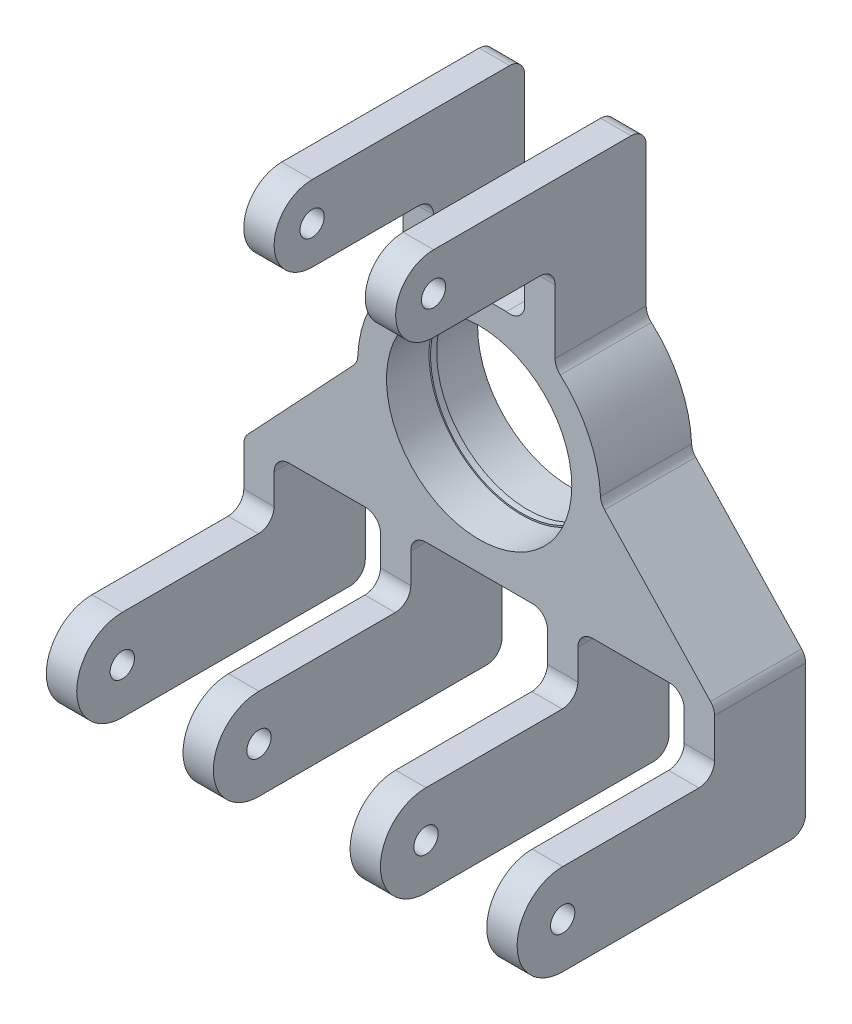
SolidWorks part; units mm, degrees
ref_plane "Front Plane" through (0, 0, 0) normal (0, 0, 1) x (1, 0, 0)
ref_plane "Top Plane" through (0, 0, 0) normal (0, 1, 0) x (1, 0, 0)
ref_plane "Right Plane" through (0, 0, 0) normal (1, 0, 0) x (0, 0, -1)
sketch "Sketch1" plane through (0, 0, 0) normal (0, 0, 1) x (1, 0, 0)
  line L0 (-15, 84.641) -> (-15, 43.7894)
  line L1 (0, -40) -> (0, -90) construction
  line L2 (15, 84.641) -> (25, 84.641)
  line L3 (76.1661, -38.5772) -> (41.2895, -1.3754)
  line L4 (67.5, -90) -> (77.5, -90)
  line L5 (25, 84.641) -> (25, 33.6115)
  line L6 (-25, 84.641) -> (-25, 33.6115)
  line L7 (-37.432, -40) -> (-62.568, -40)
  line L8 (15, 84.641) -> (15, 43.7894)
  line L9 (-25, 84.641) -> (-15, 84.641)
  line L10 (22.5, -90) -> (32.5, -90)
  line L11 (77.5, -90) -> (77.5, -41.9503)
  line L12 (67.5, -90) -> (67.5, -44.932)
  line L14 (32.5, -90) -> (32.5, -44.932)
  line L15 (37.432, -40) -> (62.568, -40)
  line L16 (22.5, -90) -> (22.5, -44.932)
  line L17 (-32.5, -90) -> (-22.5, -90)
  line L18 (17.568, -40) -> (-17.568, -40)
  line L19 (-22.5, -44.932) -> (-22.5, -90)
  line L20 (-77.5, -90) -> (-67.5, -90)
  line L21 (-32.5, -90) -> (-32.5, -44.932)
  line L22 (-67.5, -44.932) -> (-67.5, -90)
  line L23 (-8.9629, 38.9829) -> (8.9629, 38.9829)
  line L24 (-77.5, -90) -> (-77.5, -41.9503)
  line L25 (-76.1661, -38.5772) -> (-41.2895, -1.3754)
  line L26 (70.6196, -14.9692) -> (62.568, -24.0726)
  line L29 (31.5757, 50.4604) -> (25, 33.6115)
  circle A0 centre (0, 0) radius 31
  arc A1 (39.9604, 1.7784) -> (26.7132, 29.7725) centre (0, 0) ccw
  arc A2 (-77.5, -41.9503) -> (-76.1661, -38.5772) centre (-72.568, -41.9503) cw
  arc A3 (77.5, -41.9503) -> (76.1661, -38.5772) centre (72.568, -41.9503) ccw
  arc A4 (67.5, -44.932) -> (62.568, -40) centre (62.568, -44.932) ccw
  arc A5 (37.432, -40) -> (32.5, -44.932) centre (37.432, -44.932) ccw
  arc A6 (22.5, -44.932) -> (17.568, -40) centre (17.568, -44.932) ccw
  arc A7 (-17.568, -40) -> (-22.5, -44.932) centre (-17.568, -44.932) ccw
  arc A8 (-32.5, -44.932) -> (-37.432, -40) centre (-37.432, -44.932) ccw
  arc A9 (-62.568, -40) -> (-67.5, -44.932) centre (-62.568, -44.932) ccw
  arc A11 (-26.7132, 29.7725) -> (-39.9604, 1.7784) centre (0, 0) ccw
  arc A12 (-39.9604, 1.7784) -> (-41.2895, -1.3754) centre (-44.8875, 1.9977) cw
  arc A13 (41.2895, -1.3754) -> (39.9604, 1.7784) centre (44.8875, 1.9977) cw
  arc A14 (15, 43.7894) -> (8.9629, 38.9829) centre (10.068, 43.7894) cw
  arc A15 (-15, 43.7894) -> (-8.9629, 38.9829) centre (-10.068, 43.7894) ccw
  arc A16 (26.7132, 29.7725) -> (25, 33.6115) centre (30.1577, 33.6115) cw
  arc A17 (-26.7132, 29.7725) -> (-25, 33.6115) centre (-30.1577, 33.6115) ccw
  circle A21 centre (65.0017, -10.0004) radius 7.5
  circle A22 centre (65.0017, -10.0004) radius 5
  circle A24 centre (38.5625, 47.7336) radius 7.5
  circle A25 centre (38.5625, 47.7336) radius 5
  arc A26 (44.835, 43.6219) -> (65.9863, -2.5653) centre (69.9248, 27.175) ccw
  point P7 (0, 40)
  point P12 (-20, 84.641)
  point P15 (-20, 84.641)
  point P17 (-77.5, -40)
  point P18 (20, 84.641)
  point P22 (77.5, -40)
  point P27 (20, 84.641)
  point P32 (0, -90)
  point P33 (27.5, -90)
  point P35 (-27.5, -90)
  point P38 (72.5, -90)
  point P41 (27.5, -90)
  point P48 (-27.5, -90)
  point P52 (-72.5, -90)
  point P63 (-40, 0)
  point P66 (40, 0)
  point P69 (15, 37.081)
  point P72 (-15, 37.081)
  point P77 (-25, 31.225)
  point P78 (56.685, -17.7973)
  dimension "D1" = 80
  dimension "D2" = 62
  dimension "D3" = 4.932
  dimension "D4" = 10
  dimension "D8" = 4.932
  dimension "D6" = 4.932
  dimension "D7" = 4.932
  dimension "D10" = 5.1577
  dimension "D11" = 22.51
  dimension "D18" = 15
  dimension "D19" = 10
  dimension "D22" = 15
  dimension "D23" = 10
  dimension "D16" = 30
  dimension "D5" = 50
  dimension "D9" = 10
  dimension "D12" = 10
  dimension "D13" = 10
  dimension "D14" = 50
  dimension "D15" = 10
  dimension "D20" = 63.5
  dimension "D21" = 19.58
extrude "Boss-Extrude2" add sketch "Sketch1" along normal blind 30 contours L23 A14 L8 L2 L5 A16 A1 A13 L3 A3 L11 L4 L12 A4 L15 A5 L14 L10 L16 A6 L18 A7 L19 L17 L21 A8 L7 A9 L22 L20 L24 A2 L25 A12 A11 A17 L6 L9 L0 A15
sketch3d "3DSketch1"
  line L0 (25, 33.6115, 0) -> (55.1201, 33.6115, 0)
  line L1 (37.5535, 42.2929, 0) -> (47.5535, 42.2929, 0) construction
  line L2 (42.5535, 47.2929, 0) -> (42.5535, 37.2929, 0) construction
  line L3 (58.9178, -17.2632, 0) -> (70.2491, -17.2632, 0) construction
  line L4 (74.516, -36.8171, 0) -> (41.2895, -1.3754, 0)
  line L5 (64.5834, -11.5976, 0) -> (64.5834, -22.9289, 0) construction
  line L6 (78.9863, -32.6262, 0) -> (74.516, -36.8171, 0)
  line L7 (36.9074, 47.2297, 0) -> (25, 33.6115, 0)
  line L8 (25, 33.6115, 0) -> (42.5535, 42.2929, 0)
  circle A1 centre (42.5535, 42.2929, 0) radius 5
  circle A4 centre (64.5834, -17.2632, 0) radius 5.6657
  circle A5 centre (42.5535, 42.2929, 0) radius 7.5
  arc A6 (48.0997, 37.2442, 0) -> (57.9491, 2.723, 0) centre (61.5074, 22.4039, 0) cw
  arc A8 (25, 33.6115, 0) -> (26.7132, 29.7725, 0) centre (30.1577, 33.6115, 0) cw
  circle A9 centre (64.5834, -17.2632, 0) radius 21.0586
  arc A10 (26.7132, 29.7725, 0) -> (39.9604, 1.7784, 0) centre (0, 0, 0) ccw
  arc A11 (41.2895, -1.3754, 0) -> (39.9604, 1.7784, 0) centre (44.8875, 1.9977, 0) ccw
  point P7 (42.5535, 42.2929, 0)
  point P8 (42.5535, 42.2929, 0)
  point P11 (42.5535, 42.2929, 5)
  point P17 (64.5834, -17.2632, 5.6657)
  point P20 (42.5535, 42.2929, 0)
  point P24 (64.5834, -17.2632, 0)
  point P27 (64.5834, -17.2632, 0)
  point P29 (64.5834, -17.2632, 21.0586)
  point P31 (42.5535, 42.2929, 7.5)
  point P39 (61.5074, 22.4039, 20)
  point P45 (30.1577, 33.6115, 5.1577)
  point P49 (0, 0, -40)
  point P53 (44.8875, 1.9977, -4.932)
  dimension "D2" = 63.5
  dimension "D1" = 26.316
sketch "Sketch2" plane through (-77.5, 0, 0) normal (-1, 0, 0) x (0, 0, 1)
  line L0 (30, -90) -> (80, -90)
  line L1 (30, -90) -> (4.932, -90)
  line L2 (80, -60) -> (35.1577, -60)
  line L3 (30, -41.9503) -> (30, -90) construction
  line L4 (0, -85.068) -> (0, -41.9503)
  line L5 (30, -54.8423) -> (30, -41.9503)
  arc A0 (80, -90) -> (80, -60) centre (80, -75) ccw
  circle A1 centre (80, -75) radius 4
  arc A2 (4.932, -90) -> (0, -85.068) centre (4.932, -85.068) cw
  arc A3 (35.1577, -60) -> (30, -54.8423) centre (35.1577, -54.8423) cw
  point P16 (0, -90)
  point P21 (30, -60)
  line M6 (30, -90) -> (30, -41.9503)
  dimension "D3" = 8
  dimension "D4" = 4.932
  dimension "D5" = 5.1577
  dimension "D1" = 50
  dimension "D2" = 30
extrude "Boss-Extrude3" add sketch "Sketch2" against normal blind 10 contours L0 A0 L2 A1 M6
sketch "Sketch3" plane through (-77.5, 0, 0) normal (-1, 0, 0) x (0, 0, 1)
  line L0 (0, -85) -> (0, -66.5929)
  line L1 (0, -41.9503) -> (0, -90) construction
  line L2 (5, -90) -> (19.0875, -90)
  line L3 (80, -90) -> (0, -90) construction
  line L4 (0, -85) -> (0, -90)
  line L5 (0, -90) -> (5, -90)
  arc A0 (5, -90) -> (0, -85) centre (5, -85) cw
  point P10 (0, -90)
  line M4 (0, -41.9503) -> (0, -90)
  line M5 (0, -90) -> (80, -90)
  dimension "D1" = 5
extrude "Cut-Extrude3" cut sketch "Sketch3" against normal blind 162 contours A0 M5 M4
sketch "Sketch4" plane through (-32.5, 0, 0) normal (-1, 0, 0) x (0, 0, 1)
  line L0 (30, -90) -> (80, -90)
  line L1 (80, -60) -> (35.1577, -60)
  arc A0 (80, -90) -> (80, -60) centre (80, -75) ccw
  circle A1 centre (80, -75) radius 4
  arc A2 (35.1577, -60) -> (30, -54.8423) centre (35.1577, -54.8423) cw
  line M7 (30, -90) -> (30, -44.932)
  dimension "D1" = 30
  dimension "D2" = 8
extrude "Boss-Extrude4" add sketch "Sketch4" against normal blind 10 contours L1 A2 L0 A0 A1 M7
sketch "Sketch5" plane through (22.5, 0, 0) normal (-1, 0, 0) x (0, 0, 1)
  line L0 (30, -90) -> (80, -90)
  line L1 (80, -60) -> (35.1577, -60)
  arc A0 (80, -90) -> (80, -60) centre (80, -75) ccw
  circle A1 centre (80, -75) radius 4
  arc A2 (35.1577, -60) -> (30, -54.8423) centre (35.1577, -54.8423) cw
  line M4 (30, -90) -> (30, -44.932)
  dimension "D1" = 8
extrude "Boss-Extrude5" add sketch "Sketch5" against normal blind 10 contours L1 A2 L0 A0 A1 M4
sketch "Sketch6" plane through (67.5, 0, 0) normal (-1, 0, 0) x (0, 0, 1)
  line L0 (30, -90) -> (80, -90)
  line L1 (80, -60) -> (35.1577, -60)
  arc A0 (80, -90) -> (80, -60) centre (80, -75) ccw
  circle A1 centre (80, -75) radius 4
  arc A2 (35.1577, -60) -> (30, -54.8423) centre (35.1577, -54.8423) cw
  line M4 (30, -90) -> (30, -44.932)
  dimension "D1" = 8
extrude "Boss-Extrude6" add sketch "Sketch6" against normal blind 10 contours L1 A2 L0 A0 A1 M4
sketch "Sketch7" plane through (-25, 0, 0) normal (-1, 0, 0) x (0, 0, 1)
  line L0 (30, 84.641) -> (70, 84.641)
  line L1 (30, 54.641) -> (30, 49.8065)
  line L2 (70, 59.641) -> (35, 59.641)
  line L3 (30, 84.641) -> (30, 33.6115) construction
  line L4 (30, 84.641) -> (30, 33.6115) construction
  arc A0 (70, 59.641) -> (70, 84.641) centre (70, 72.141) ccw
  circle A1 centre (70, 72.141) radius 4
  arc A2 (30, 54.641) -> (35, 59.641) centre (35, 54.641) cw
  point P14 (30, 59.641)
  line M5 (30, 33.6115) -> (30, 84.641)
  dimension "D3" = 8
  dimension "D4" = 5
  dimension "D1" = 40
  dimension "D2" = 25
extrude "Boss-Extrude7" add sketch "Sketch7" against normal blind 10 contours L2 A0 L0 A1 M5
sketch "Sketch9" plane through (-25, 0, 0) normal (-1, 0, 0) x (0, 0, 1)
  line L0 (0, 79.641) -> (0, 74.0205)
  line L1 (0, 84.641) -> (0, 33.6115) construction
  line L2 (5, 84.641) -> (12.5703, 84.641)
  line L3 (70, 84.641) -> (0, 84.641) construction
  arc A0 (5, 84.641) -> (0, 79.641) centre (5, 79.641) ccw
  point P10 (0, 84.641)
  dimension "D1" = 5
extrude "Cut-Extrude4" cut sketch "Sketch9" against normal blind 57 and the other way through all
sketch "Sketch13" plane through (15, 0, 0) normal (-1, 0, 0) x (0, 0, 1)
  line L0 (30, 84.641) -> (70, 84.641)
  line L1 (30, 54.641) -> (30, 49.8065)
  line L2 (70, 59.641) -> (35, 59.641)
  arc A0 (70, 59.641) -> (70, 84.641) centre (70, 72.141) ccw
  circle A1 centre (70, 72.141) radius 4
  arc A2 (30, 54.641) -> (35, 59.641) centre (35, 54.641) cw
  line M4 (30, 43.7894) -> (30, 84.641)
  dimension "D3" = 8
  dimension "D4" = 5
  dimension "D1" = 40
  dimension "D2" = 25
extrude "Boss-Extrude8" add sketch "Sketch13" against normal blind 10 contours A2 L2 A0 L0 A1 M4
sketch "Sketch14" plane through (0, 0, 30) normal (0, 0, 1) x (1, 0, 0)
  circle A0 centre (0, 0) radius 30.5
  circle A1 centre (0, 0) radius 30
  dimension "D1" = 61
  dimension "D2" = 60
extrude "Cut-Extrude5" cut sketch "Sketch14" against normal through all contours A1
sketch "Sketch15" plane through (0, 0, 30) normal (0, 0, 1) x (1, 0, 0)
  circle A0 centre (0, 0) radius 30.5
  dimension "D1" = 61
extrude "Cut-Extrude6" cut sketch "Sketch15" against normal blind 14 contours A0
sketch "Sketch16" plane through (0, 0, 0) normal (0, 0, -1) x (-1, 0, 0)
  circle A0 centre (0, 0) radius 30.5
  dimension "D1" = 61
extrude "Cut-Extrude7" cut sketch "Sketch16" against normal blind 14 contours A0
